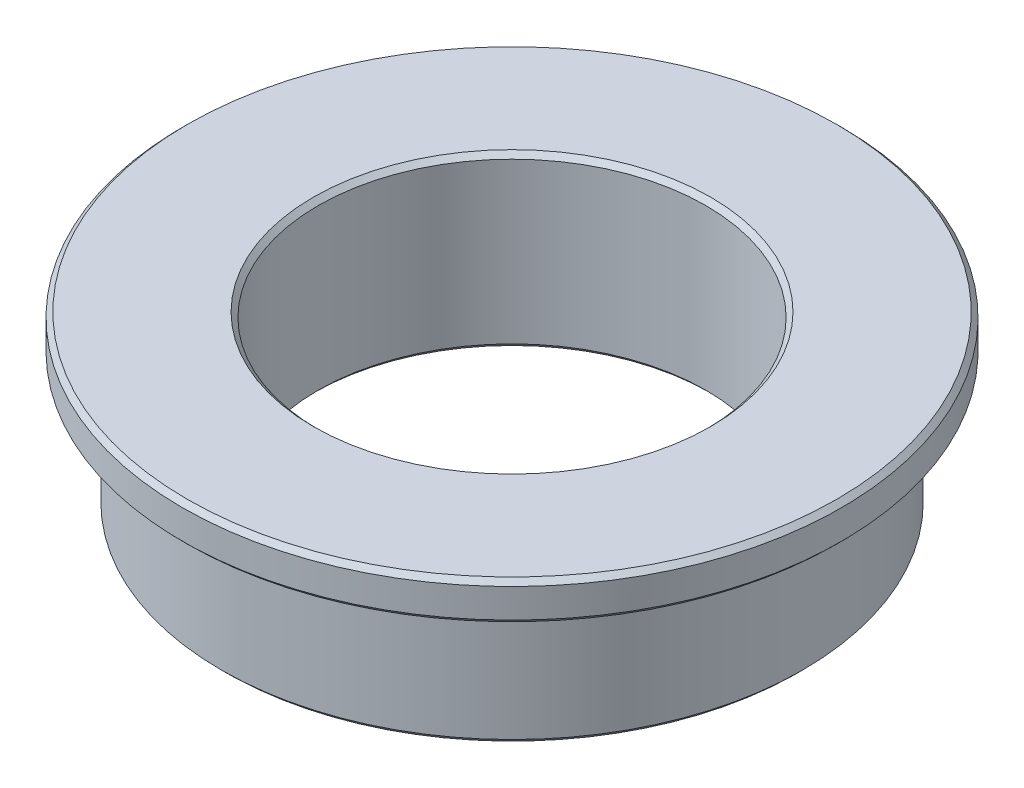
SolidWorks part; units mm, degrees
material "不锈钢 (铁素体)"
ref_plane "前视基准面" through (0, 0, 0) normal (0, 0, 1) x (1, 0, 0)
ref_plane "上视基准面" through (0, 0, 0) normal (0, 1, 0) x (1, 0, 0)
ref_plane "右视基准面" through (0, 0, 0) normal (1, 0, 0) x (0, 0, -1)
sketch "草图1" plane through (0, 0, 0) normal (0, 0, 1) x (1, 0, 0)
  line L0 (0, 0) -> (0, 11058.4157) construction
  line L1 (0, 0) -> (11058.4157, 0) construction
  line L2 (6, 0) -> (6, 2.7)
  line L3 (6, 2.7) -> (6.8, 2.7)
  line L4 (6.8, 2.7) -> (6.8, 3.5)
  line L5 (6.8, 3.5) -> (4, 3.5)
  line L6 (4, 3.5) -> (4, 0)
  line L7 (4, 0) -> (6, 0)
  dimension "D1" = 8
  dimension "D2" = 12
  dimension "D3" = 13.6
  dimension "D4" = 3.5
  dimension "D5" = 0.8
revolve "旋转1" add sketch "草图1" angle 360 about L0
chamfer "倒角1" distance 0.1 angle 45 5 edges at (0, 0, -6) (0, 0, -4) (0, 2.7, -6.8) (0, 3.5, -6.8) (0, 3.5, -4)
